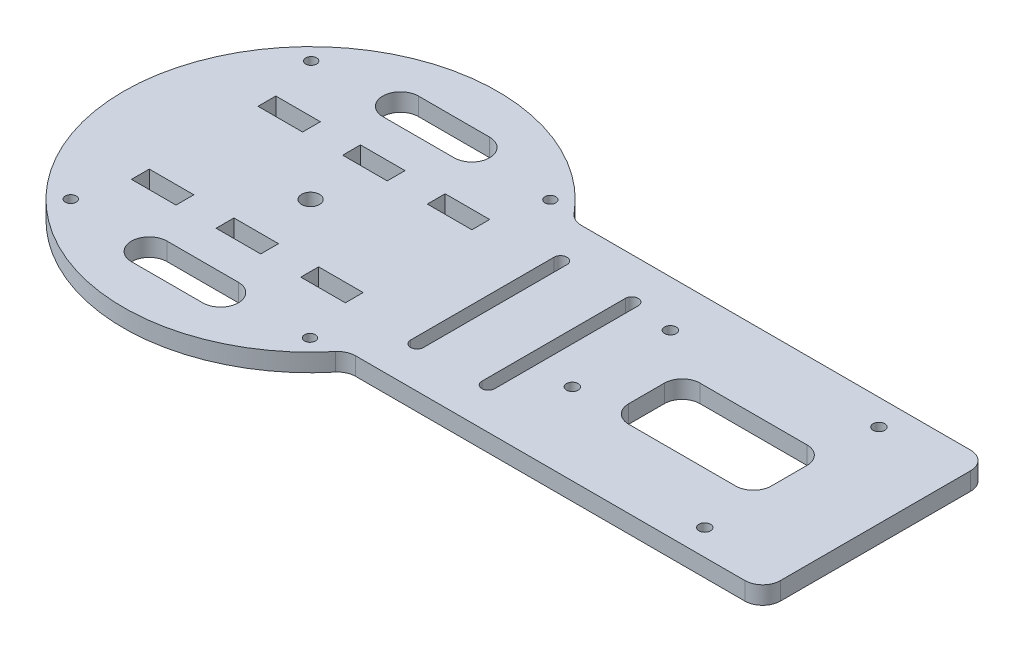
SolidWorks part; units mm, degrees
ref_plane "前视基准面" through (0, 0, 0) normal (0, 0, 1) x (1, 0, 0)
ref_plane "上视基准面" through (0, 0, 0) normal (0, 1, 0) x (1, 0, 0)
ref_plane "右视基准面" through (0, 0, 0) normal (1, 0, 0) x (0, 0, -1)
sketch "草图1" plane through (0, 0, 0) normal (0, 1, 0) x (1, 0, 0)
  line L0 (0, 0) -> (0, 59606) construction
  line L1 (0, 0) -> (59606, 0) construction
  line L2 (30, -20.25) -> (30, -15.25)
  line L3 (-30, 20.25) -> (-17.5, 20.25)
  line L4 (-30, 20.25) -> (-30, 15.25)
  line L5 (-30, 15.25) -> (-17.5, 15.25)
  line L6 (-17.5, 20.25) -> (-17.5, 15.25)
  line L7 (-6.25, 20.25) -> (6.25, 20.25)
  line L8 (-6.25, 20.25) -> (-6.25, 15.25)
  line L9 (-6.25, 15.25) -> (6.25, 15.25)
  line L10 (6.25, 20.25) -> (6.25, 15.25)
  line L11 (17.5, 20.25) -> (30, 20.25)
  line L12 (17.5, 20.25) -> (17.5, 15.25)
  line L13 (17.5, 15.25) -> (30, 15.25)
  line L14 (30, 20.25) -> (30, 15.25)
  line L15 (17.5, -15.25) -> (30, -15.25)
  line L16 (17.5, -20.25) -> (17.5, -15.25)
  line L17 (17.5, -20.25) -> (30, -20.25)
  line L18 (6.25, -20.25) -> (6.25, -15.25)
  line L19 (-6.25, -15.25) -> (6.25, -15.25)
  line L20 (-6.25, -20.25) -> (-6.25, -15.25)
  line L21 (-6.25, -20.25) -> (6.25, -20.25)
  line L22 (-17.5, -20.25) -> (-17.5, -15.25)
  line L23 (-30, -15.25) -> (-17.5, -15.25)
  line L24 (-30, -20.25) -> (-30, -15.25)
  line L25 (-30, -20.25) -> (-17.5, -20.25)
  line L26 (-10, -30.25) -> (10, -30.25)
  line L27 (-10, -40.25) -> (10, -40.25)
  line L28 (-10, 40.25) -> (10, 40.25)
  line L29 (-10, 30.25) -> (10, 30.25)
  line L30 (41.8682, 31.675) -> (158.5, 31.675)
  line L31 (41.8682, -31.675) -> (158.5, -31.675)
  line L32 (158.5, 31.675) -> (158.5, -31.675)
  line L33 (48.1838, 20.1251) -> (48.1838, -20.1251)
  line L34 (51.8162, 20.1251) -> (51.8162, -20.1251)
  line L35 (68.1838, 20.1251) -> (68.1838, -20.1251)
  line L36 (71.8162, 20.1251) -> (71.8162, -20.1251)
  line L38 (94.25, 10) -> (134.25, 10)
  line L39 (94.25, 10) -> (94.25, -10)
  line L40 (94.25, -10) -> (134.25, -10)
  line L41 (134.25, 10) -> (134.25, -10)
  arc A0 (41.8682, 31.675) -> (41.8682, -31.675) centre (0, 0) ccw
  circle A1 centre (-33.5536, 33.7209) radius 1.525
  circle A5 centre (0, 0) radius 2.5
  arc A6 (-10, -30.25) -> (-10, -40.25) centre (-10, -35.25) ccw
  arc A7 (10, -40.25) -> (10, -30.25) centre (10, -35.25) ccw
  arc A8 (10, 40.25) -> (10, 30.25) centre (10, 35.25) cw
  arc A9 (-10, 30.25) -> (-10, 40.25) centre (-10, 35.25) cw
  arc A10 (51.8162, 20.1251) -> (48.1838, 20.1251) centre (50, 20.1251) ccw
  arc A11 (71.8162, 20.1251) -> (68.1838, 20.1251) centre (70, 20.1251) ccw
  arc A12 (71.8162, -20.1251) -> (68.1838, -20.1251) centre (70, -20.1251) cw
  arc A13 (51.8162, -20.1251) -> (48.1838, -20.1251) centre (50, -20.1251) cw
  circle A14 centre (82.254, 18.675) radius 1.625
  circle A15 centre (82.254, -8.825) radius 1.625
  circle A16 centre (135, 24.425) radius 1.625
  circle A17 centre (135, -24.425) radius 1.625
  circle A19 centre (33.7209, 33.5536) radius 1.525
  circle A20 centre (33.5536, -33.7209) radius 1.525
  circle A21 centre (-33.7209, -33.5536) radius 1.525
  point P28 (-6.25, 17.75)
  point P29 (6.25, 17.75)
  point P84 (0, 0)
  dimension "D1" = 105
  dimension "D2" = 3.05
  dimension "D10" = 5
  dimension "D11" = 10
  dimension "D21" = 3.25
  dimension "D24" = 3.25
  dimension "D3" = 4
  dimension "D4" = 30.5
  dimension "D5" = 12.5
  dimension "D6" = 5
  dimension "D8" = 11.25
  dimension "D9" = 11.25
  dimension "D12" = 20
  dimension "D13" = 63.35
  dimension "D14" = 50
  dimension "D15" = 20
  dimension "D16" = 20
  dimension "D17" = 40
  dimension "D18" = 24.25
  dimension "D19" = 158.5
  dimension "D20" = 13
  dimension "D22" = 82.254
  dimension "D23" = 27.5
  dimension "D25" = 48.85
  dimension "D26" = 23.5
  dimension "D28" = 70.5
extrude "凸台-拉伸1" add sketch "草图1" along normal blind 5
fillet "圆角1" radius 5 8 edges at (41.8682, 2.5, -31.675) (158.5, 2.5, -31.675) (158.5, 2.5, 31.675) (41.8682, 2.5, 31.675) (134.25, 2.5, 10) (134.25, 2.5, -10) (94.25, 2.5, 10) (94.25, 2.5, -10)
